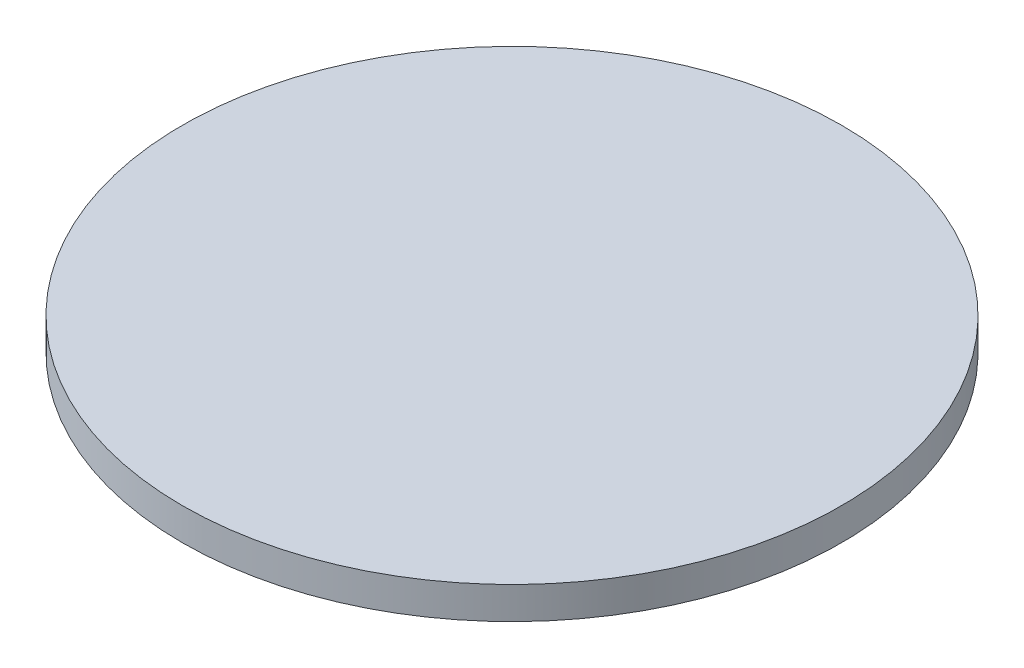
SolidWorks part; units mm, degrees
ref_plane "Front Plane" through (0, 0, 0) normal (0, 0, 1) x (1, 0, 0)
ref_plane "Top Plane" through (0, 0, 0) normal (0, 1, 0) x (1, 0, 0)
ref_plane "Right Plane" through (0, 0, 0) normal (1, 0, 0) x (0, 0, -1)
sketch "Sketch1" plane through (0, 0, 0) normal (0, 1, 0) x (1, 0, 0)
  circle A0 centre (0, 0) radius 30.75
  dimension "D1" = 61.5
extrude "Boss-Extrude1" add sketch "Sketch1" along normal blind 3
